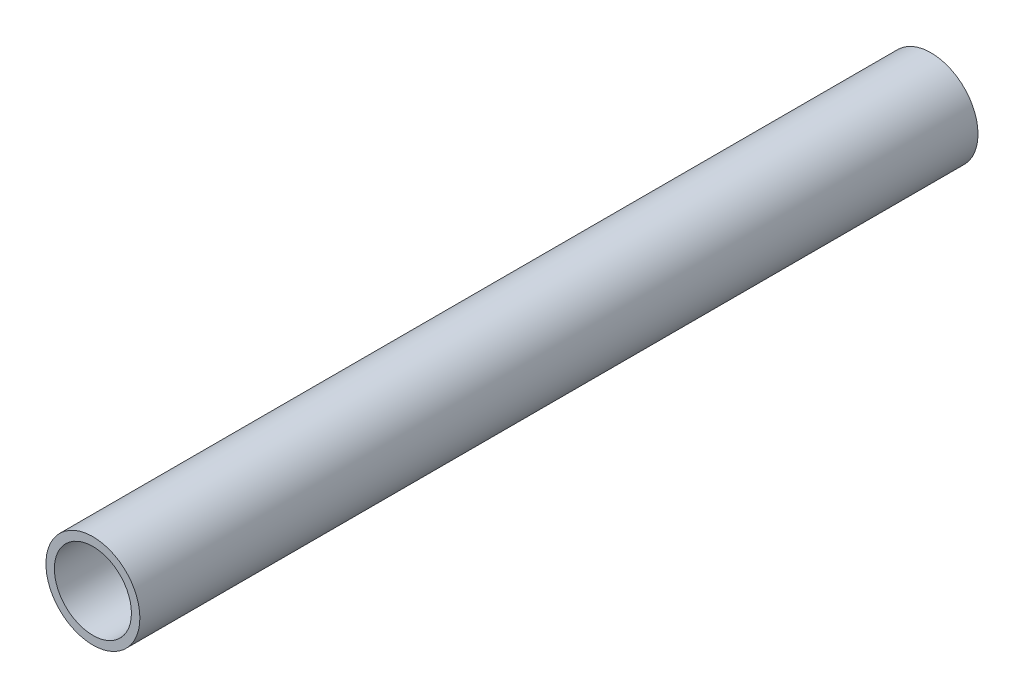
SolidWorks part; units mm, degrees
ref_plane "Face" through (0, 0, 0) normal (0, 0, 1) x (1, 0, 0)
ref_plane "Dessus" through (0, 0, 0) normal (0, 1, 0) x (1, 0, 0)
ref_plane "Droite" through (0, 0, 0) normal (1, 0, 0) x (0, 0, -1)
sketch "Esquisse1" plane through (0, 0, 0) normal (0, 0, 1) x (1, 0, 0)
  circle A0 centre (0, 0) radius 4.1
  circle A1 centre (0, 0) radius 5
  dimension "D1" = 8.2
  dimension "D2" = 10
extrude "Boss.-Extru.1" add sketch "Esquisse1" along normal mid plane 89.2
